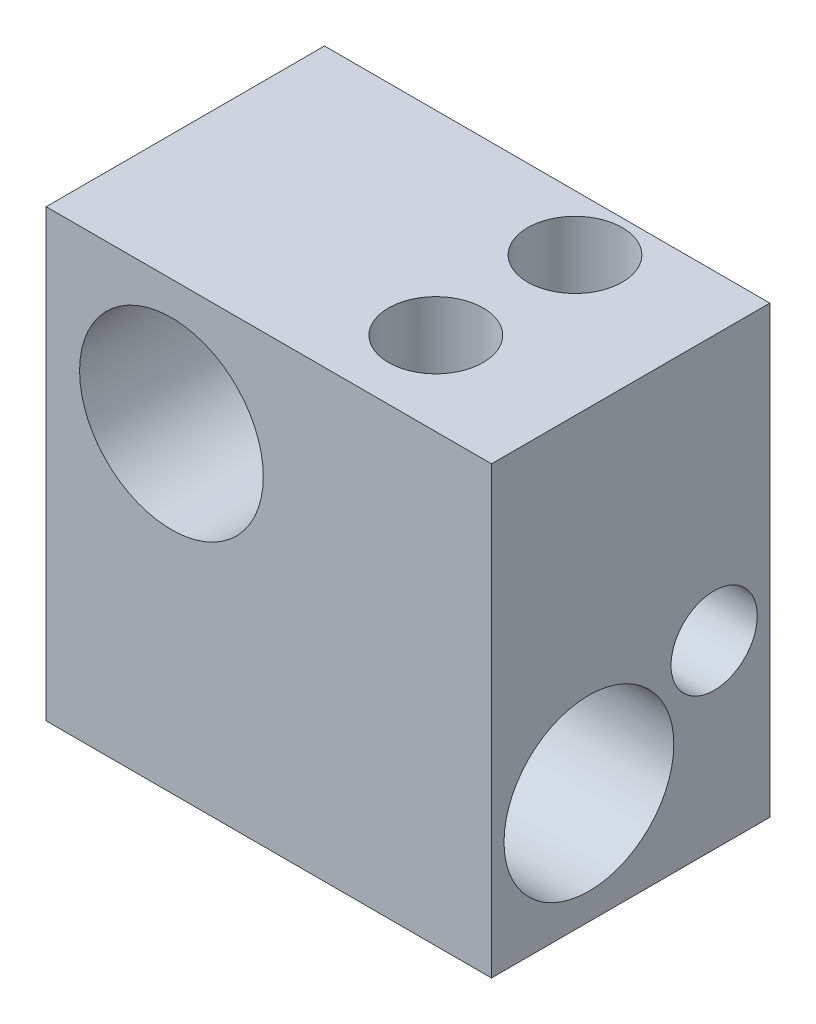
SolidWorks part; units mm, degrees
ref_plane "Plan de face" through (0, 0, 0) normal (0, 0, 1) x (1, 0, 0)
ref_plane "Plan de dessus" through (0, 0, 0) normal (0, 1, 0) x (1, 0, 0)
ref_plane "Plan de droite" through (0, 0, 0) normal (1, 0, 0) x (0, 0, -1)
sketch "Esquisse1" plane through (0, 0, 0) normal (0, 0, 1) x (1, 0, 0)
  line L1 (0, 0) -> (16, 0)
  line L2 (0, 0) -> (0, 16)
  line L3 (0, 16) -> (16, 16)
  line L4 (16, 0) -> (16, 16)
  dimension "D1" = 16
  dimension "D2" = 16
extrude "Boss.-Extru.1" add sketch "Esquisse1" along normal blind 10
sketch "Esquisse2" plane through (0, 0, 10) normal (0, 0, 1) x (1, 0, 0)
  line L0 (16, 16) -> (0, 16) construction
  line L1 (0, 16) -> (0, 0) construction
  circle A0 centre (4.5, 11.5) radius 3
  point P6 (0.941, 10.6125)
  point P9 (4.8261, 9.6619)
  dimension "D1" = 6
  dimension "D2" = 4.5
  dimension "D3" = 4.5
hole_wizard "Dégagement M61" positions "Esquisse4" profile "Esquisse3" hole size "M6" standard "ISO" end condition through all
sketch "Esquisse4" plane through (0, 0, 10) normal (0, 0, 1) x (1, 0, 0)
  point P0 (4.5, 11.5)
sketch "Esquisse3" plane through (4.5, 11.5, 10) normal (1, 0, 0) x (0, -1, 0)
  line L0 (0, 0) -> (0, 10)
  line L1 (0, 10) -> (3.3, 10)
  line L2 (3.3, 10) -> (3.3, 0)
  line L5 (3.3, 0) -> (0, 0)
  line L11 (0, -6.35) -> (0, 107.95) construction
  dimension "Diamètre du perçage jusqu'au prochain" = 6.6
  dimension "Profondeur du perçage jusqu'au prochain" = 10
sketch "Esquisse5" plane through (16, 0, 0) normal (1, 0, 0) x (0, 0, -1)
  line L0 (-10, 0) -> (-10, 16) construction
  line L1 (-10, 0) -> (0, 0) construction
  line L2 (0, 0) -> (0, 16) construction
  circle A0 centre (-6.5, 4) radius 3
  circle A1 centre (-2, 6.5) radius 1.5
  dimension "D3" = 6
  dimension "D6" = 3
  dimension "D1" = 3.5
  dimension "D2" = 4
  dimension "D4" = 6.5
  dimension "D5" = 2
hole_wizard "Diamètre du perçage Ø6.1 (6.1)1" positions "Esquisse7" profile "Esquisse6" hole size "Ø6.1" standard "ISO" end condition through all
sketch "Esquisse7" plane through (16, 0, 0) normal (1, 0, 0) x (0, 0, -1)
  point P0 (-6.5, 4)
sketch "Esquisse6" plane through (16, 4, 6.5) normal (0, 1, 0) x (0, 0, -1)
  line L0 (0, 0) -> (0, 16)
  line L1 (0, 16) -> (3.05, 16)
  line L2 (3.05, 16) -> (3.05, 0)
  line L5 (3.05, 0) -> (0, 0)
  line L11 (0, -6.35) -> (0, 107.95) construction
  dimension "Diamètre du perçage jusqu'au prochain" = 6.1
  dimension "Profondeur du perçage jusqu'au prochain" = 16
hole_wizard "Diamètre du perçage Ø3.1 (3.1)1" positions "Esquisse9" profile "Esquisse8" hole size "Ø3.1" standard "ISO" end condition through all
sketch "Esquisse9" plane through (16, 0, 0) normal (1, 0, 0) x (0, 0, -1)
  point P0 (-2, 6.5)
sketch "Esquisse8" plane through (16, 6.5, 2) normal (0, 1, 0) x (0, 0, -1)
  line L0 (0, 0) -> (0, 16)
  line L1 (0, 16) -> (1.55, 16)
  line L2 (1.55, 16) -> (1.55, 0)
  line L5 (1.55, 0) -> (0, 0)
  line L11 (0, -6.35) -> (0, 107.95) construction
  dimension "Diamètre du perçage jusqu'au prochain" = 3.1
  dimension "Profondeur du perçage jusqu'au prochain" = 16
sketch "Esquisse10" plane through (0, 16, 0) normal (0, 1, 0) x (1, 0, 0)
  line L1 (16, -10) -> (16, 0) construction
  line L2 (16, 0) -> (0, 0) construction
  line L3 (16, -10) -> (0, -10) construction
  circle A0 centre (11, -2) radius 1.5
  circle A1 centre (11, -7) radius 1.5
  dimension "D1" = 3
  dimension "D2" = 3
  dimension "D3" = 5
  dimension "D4" = 5
  dimension "D5" = 2
  dimension "D6" = 3
hole_wizard "Dégagement M31" positions "Esquisse12" profile "Esquisse11" hole size "M3" standard "ISO"
sketch "Esquisse12" plane through (0, 16, 0) normal (0, 1, 0) x (1, 0, 0)
  point P0 (11, -7)
sketch "Esquisse11" plane through (11, 16, 7) normal (1, 0, 0) x (0, 0, 1)
  line L0 (0, 0) -> (0, 12.0215)
  line L1 (0, 12.0215) -> (1.7, 11)
  line L2 (1.7, 11) -> (1.7, 0)
  line L5 (1.7, 0) -> (0, 0)
  line L10 (0, 12.0215) -> (-1.7, 11) construction
  line L11 (0, -6.35) -> (0, 107.95) construction
  dimension "Diamètre du perçage" = 3.4
  dimension "Profondeur du perçage" = 11
  dimension "Angle de pointe" = 118
hole_wizard "Dégagement M33" positions "Esquisse16" profile "Esquisse15" hole size "M3" standard "ISO"
sketch "Esquisse16" plane through (0, 16, 0) normal (0, 1, 0) x (1, 0, 0)
  point P0 (11, -2)
sketch "Esquisse15" plane through (11, 16, 2) normal (1, 0, 0) x (0, 0, 1)
  line L0 (0, 0) -> (0, 10.5215)
  line L1 (0, 10.5215) -> (1.7, 9.5)
  line L2 (1.7, 9.5) -> (1.7, 0)
  line L5 (1.7, 0) -> (0, 0)
  line L10 (0, 10.5215) -> (-1.7, 9.5) construction
  line L11 (0, -6.35) -> (0, 107.95) construction
  dimension "Diamètre du perçage" = 3.4
  dimension "Profondeur du perçage" = 9.5
  dimension "Angle de pointe" = 118
